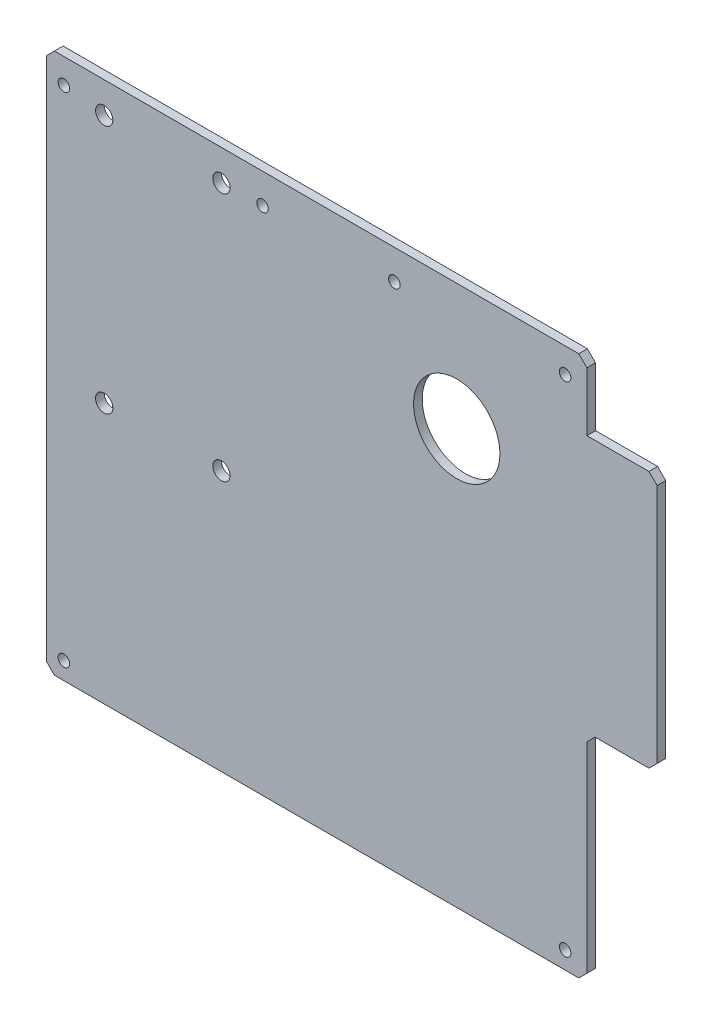
SolidWorks part; units mm, degrees
ref_plane "Front Plane" through (0, 0, 0) normal (0, 0, 1) x (1, 0, 0)
ref_plane "Top Plane" through (0, 0, 0) normal (0, 1, 0) x (1, 0, 0)
ref_plane "Right Plane" through (0, 0, 0) normal (1, 0, 0) x (0, 0, -1)
sketch "Sketch1" plane through (0, 0, 0) normal (0, 0, 1) x (1, 0, 0)
  line L0 (89.4531, 4.337) -> (-1.6432, 4.337)
  line L1 (-1.6432, 4.337) -> (-3.0574, 2.9228)
  line L2 (-3.0574, 2.9228) -> (-3.0574, -88.1735)
  line L3 (-3.0574, -88.1735) -> (-1.6432, -89.5877)
  line L4 (-1.6432, -89.5877) -> (89.4531, -89.5877)
  line L5 (89.4531, -89.5877) -> (90.8673, -88.1735)
  line L6 (90.8673, -88.1735) -> (90.8673, -53.3417)
  line L7 (90.8673, -53.3417) -> (92.2815, -51.9274)
  line L8 (92.2815, -51.9274) -> (101.6433, -51.9274)
  line L9 (101.6433, -51.9274) -> (103.0576, -50.5132)
  line L10 (103.0576, -50.5132) -> (103.0576, -8.6929)
  line L11 (103.0576, -8.6929) -> (101.6433, -7.2787)
  line L12 (101.6433, -7.2787) -> (90.8673, -7.2787)
  line L13 (90.8673, -7.2787) -> (90.8673, 2.9228)
  line L14 (90.8673, 2.9228) -> (89.4531, 4.337)
  circle A1 centre (7.0029, -1.0185) radius 1.5
  circle A2 centre (27.3718, -1.0185) radius 1.5
  circle A3 centre (34.509, -0.8681) radius 1
  circle A4 centre (57.4135, -0.8681) radius 1
  circle A5 centre (87.0794, 0.0031) radius 1
  circle A6 centre (68.2507, -17.5589) radius 7.5025
  circle A7 centre (7.0029, -44.3172) radius 1.5
  circle A8 centre (27.3718, -44.3172) radius 1.5
  circle A9 centre (0, -86.5552) radius 1
  circle A10 centre (87.0794, -86.5552) radius 1
  circle A11 centre (0, 0) radius 1
  point P2 (0, 0)
  point P3 (0, 0)
  point P5 (0, 0)
  point P8 (0, 0)
  point P10 (0, 0)
  point P12 (0, 0)
  point P14 (0, 0)
  point P15 (0, 0)
  point P18 (0, 0)
  point P20 (0, 0)
  dimension "D20" = 2
  dimension "D21" = 3
  dimension "D22" = 15.005
  dimension "D1" = 93.9248
  dimension "D2" = 93.9248
  dimension "D3" = 37.6603
  dimension "D4" = 11.6158
  dimension "D5" = 3.7879
  dimension "D6" = 3.0574
  dimension "D7" = 10.0603
  dimension "D8" = 20.3689
  dimension "D9" = 43.2988
  dimension "D10" = 5.3555
  dimension "D11" = 4.3339
  dimension "D12" = 5.2052
  dimension "D13" = 22.9045
  dimension "D14" = 7.1372
  dimension "D15" = 4.337
  dimension "D16" = 3.0325
  dimension "D17" = 12.1902
  dimension "D18" = 21.8959
  dimension "D19" = 10.8372
  dimension "D23" = 45
  dimension "D24" = 2
  dimension "D25" = 2
  dimension "D26" = 45
  dimension "D27" = 45
  dimension "D28" = 45
  dimension "D29" = 45
  dimension "D30" = 45
  dimension "D31" = 45
extrude "Boss-Extrude2" add sketch "Sketch1" along normal blind 1.5 separate body
